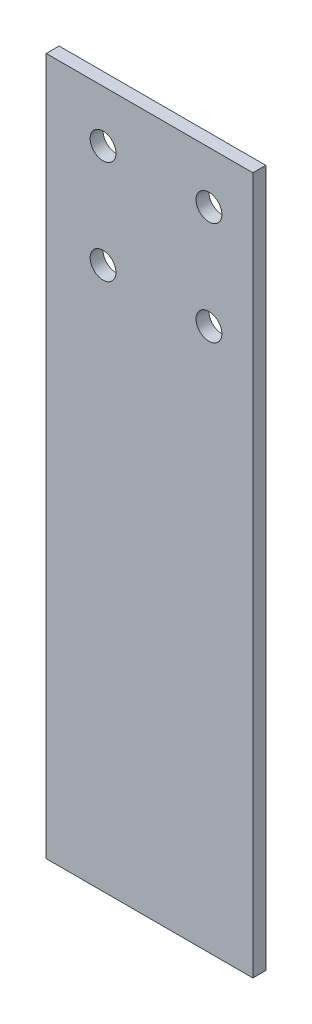
SolidWorks part; units mm, degrees
ref_plane "Front Plane" through (0, 0, 0) normal (0, 0, 1) x (1, 0, 0)
ref_plane "Top Plane" through (0, 0, 0) normal (0, 1, 0) x (1, 0, 0)
ref_plane "Right Plane" through (0, 0, 0) normal (1, 0, 0) x (0, 0, -1)
sketch "Sketch1" plane through (0, 0, 0) normal (0, 0, 1) x (1, 0, 0)
  line L0 (0, 0) -> (0, 171.45)
  line L1 (0, 171.45) -> (-50.8, 171.45)
  line L2 (-50.8, 171.45) -> (-50.8, 0)
  line L3 (-50.8, 0) -> (0, 0)
  dimension "D1" = 171.45
  dimension "D2" = 50.8
extrude "Boss-Extrude2" add sketch "Sketch1" against normal blind 3.175
sketch "Sketch2" plane through (0, 0, 0) normal (0, 0, 1) x (1, 0, 0)
  line L1 (0, 171.45) -> (-50.8, 171.45) construction
  line L2 (-50.8, 171.45) -> (-50.8, 0) construction
  circle A0 centre (-10.795, 158.75) radius 3.175
  circle A1 centre (-36.83, 158.75) radius 3.175
  circle A2 centre (-10.795, 133.35) radius 3.175
  circle A3 centre (-36.83, 133.35) radius 3.175
  point P8 (0, 0)
  point P10 (0, 0)
  point P11 (0, 0)
  point P12 (0, 0)
  point P13 (0, 0)
  point P14 (-13.97, 134.2958)
  point P15 (0, 0)
  dimension "D4" = 6.35
  dimension "D1" = 13.97
  dimension "D2" = 26.035
  dimension "D3" = 12.7
  dimension "D5" = 25.4
extrude "Cut-Extrude1" cut sketch "Sketch2" against normal through all
equation "\"D1@Boss-Extrude2\"=1/8"
